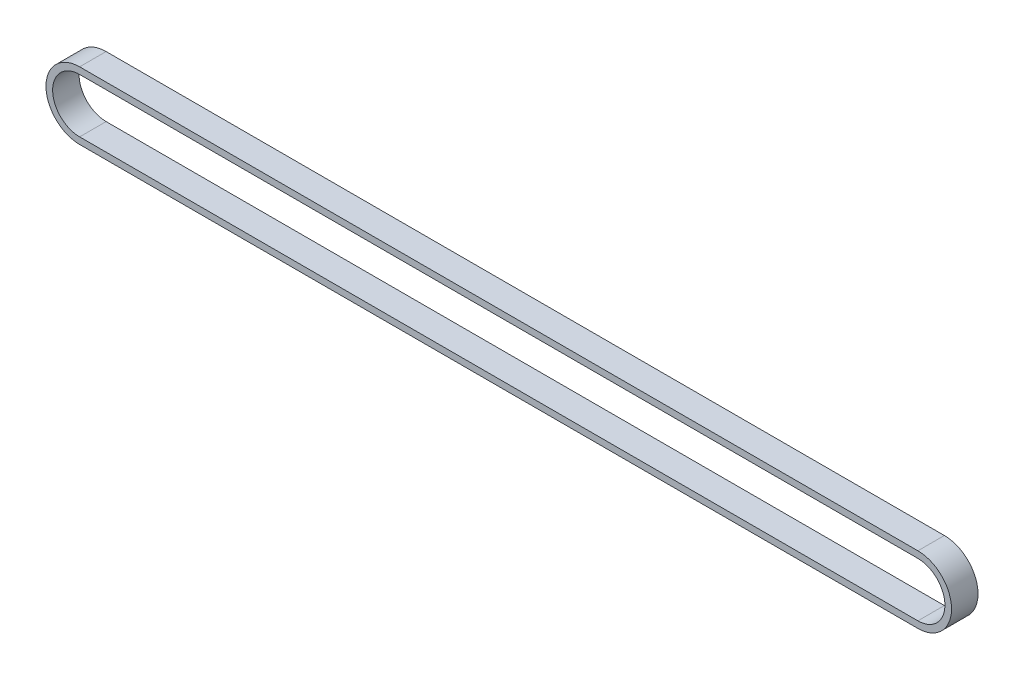
SolidWorks part; units mm, degrees
ref_plane "Front Plane" through (0, 0, 0) normal (0, 0, 1) x (1, 0, 0)
ref_plane "Top Plane" through (0, 0, 0) normal (0, 1, 0) x (1, 0, 0)
ref_plane "Right Plane" through (0, 0, 0) normal (1, 0, 0) x (0, 0, -1)
sketch "Sketch4" plane through (0, 0, 0) normal (0, 0, 1) x (1, 0, 0)
  line L0 (0, 0) -> (190, 0) construction
  line L1 (0, 6.125) -> (190, 6.125)
  line L2 (0, -6.125) -> (190, -6.125)
  line L3 (0, 0) -> (190, 0) construction
  line L4 (0, 7.625) -> (190, 7.625)
  line L5 (0, -7.625) -> (190, -7.625)
  arc A0 (0, 6.125) -> (0, -6.125) centre (0, 0) ccw
  arc A1 (190, -6.125) -> (190, 6.125) centre (190, 0) ccw
  arc A2 (0, 7.625) -> (0, -7.625) centre (0, 0) ccw
  arc A3 (190, -7.625) -> (190, 7.625) centre (190, 0) ccw
  point P3 (95, 0)
  point P10 (95, 0)
  dimension "D1" = 190
  dimension "D2" = 6.125
  dimension "D3" = 1.5
extrude "Boss-Extrude1" add sketch "Sketch4" along normal blind 6
